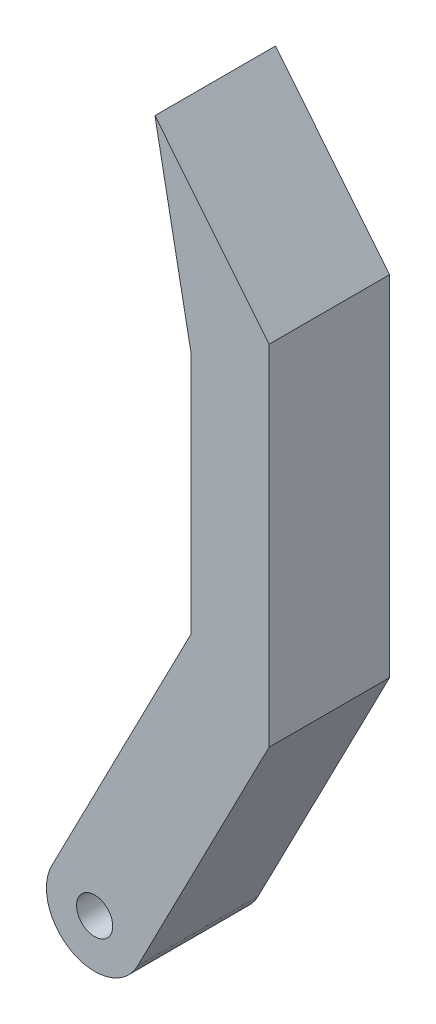
SolidWorks part; units mm, degrees
ref_plane "Front" through (0, 0, 0) normal (0, 0, 1) x (1, 0, 0)
ref_plane "Top" through (0, 0, 0) normal (0, 1, 0) x (1, 0, 0)
ref_plane "Right" through (0, 0, 0) normal (1, 0, 0) x (0, 0, -1)
sketch "草图1" plane through (0, 0, 0) normal (0, 0, 1) x (1, 0, 0)
  line L0 (8, 24.2498) -> (8, 44.4245)
  line L1 (14.47, 48.303) -> (5.0028, 60.0024)
  line L3 (3.5546, -1.8323) -> (14.47, 19.343)
  line L4 (3.5546, -1.8323) -> (3.5554, -1.8327)
  line L5 (14.47, 19.343) -> (14.47, 48.303)
  line L6 (-3.5554, 1.8327) -> (8, 24.2498)
  line L8 (8, 44.4245) -> (5.0028, 60.0024)
  circle A0 centre (0, 0) radius 1.5
  arc A1 (-3.5554, 1.8327) -> (3.5937, -1.7565) centre (0, 0) ccw
extrude "凸台-拉伸1" add sketch "草图1" along normal blind 10 contours L6 A1 L4 L3 L5 L1 L8 L0 A0
